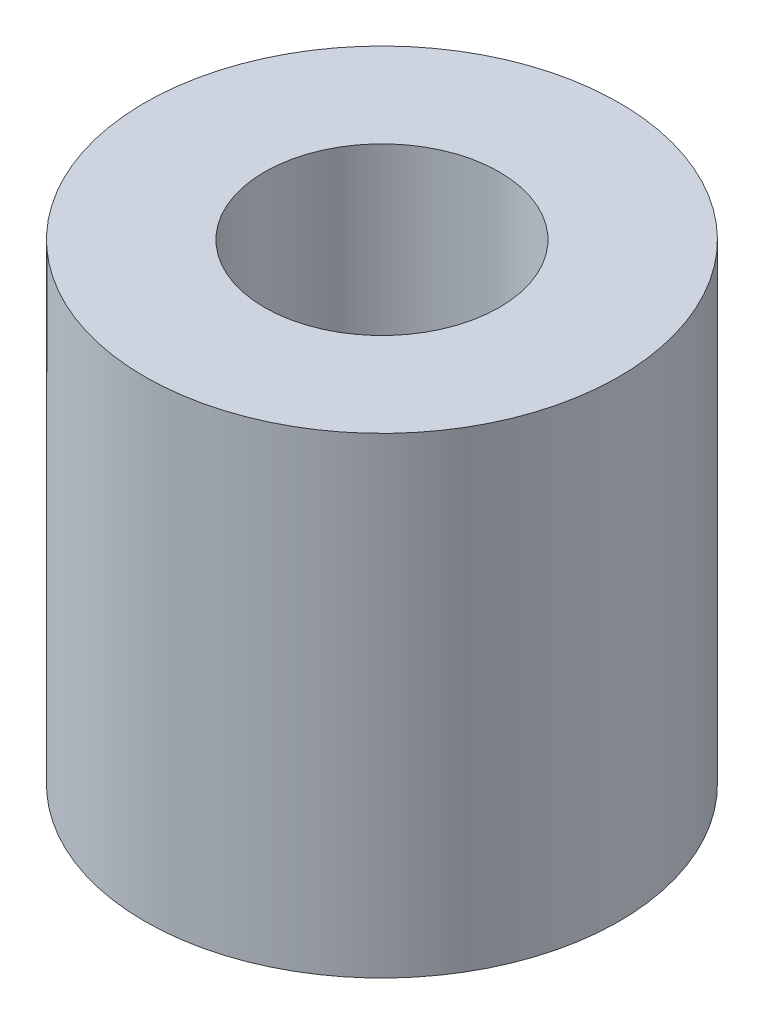
SolidWorks part; units mm, degrees
ref_plane "Front Plane" through (0, 0, 0) normal (0, 0, 1) x (1, 0, 0)
ref_plane "Top Plane" through (0, 0, 0) normal (0, 1, 0) x (1, 0, 0)
ref_plane "Right Plane" through (0, 0, 0) normal (1, 0, 0) x (0, 0, -1)
sketch "Sketch1" plane through (0, 0, 0) normal (0, 1, 0) x (1, 0, 0)
  circle A0 centre (0, 0) radius 1.2446
  circle A1 centre (0, 0) radius 2.5146
  dimension "D1" = 1.2446
  dimension "D2" = 2.5146
extrude "Boss-Extrude1" add sketch "Sketch1" along normal mid plane 5
